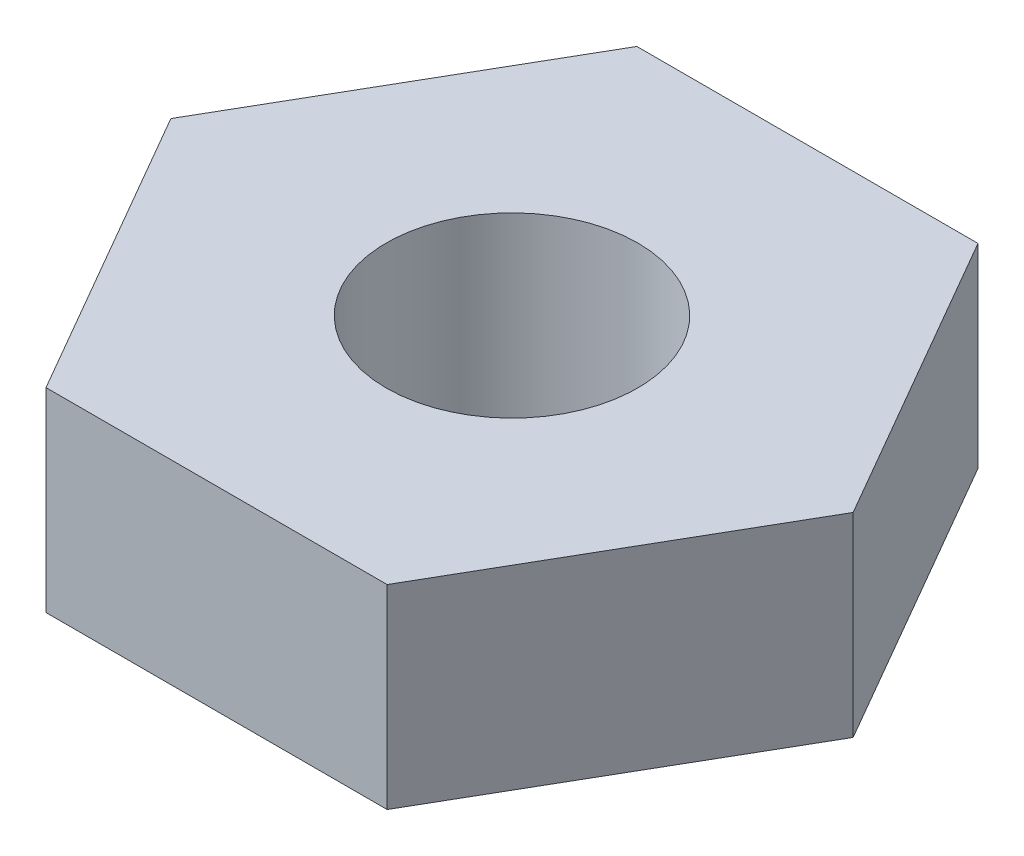
SolidWorks part; units mm, degrees
ref_plane "Front Plane" through (0, 0, 0) normal (0, 0, 1) x (1, 0, 0)
ref_plane "Top Plane" through (0, 0, 0) normal (0, 1, 0) x (1, 0, 0)
ref_plane "Right Plane" through (0, 0, 0) normal (1, 0, 0) x (0, 0, -1)
sketch "Sketch1" plane through (0, 0, 0) normal (0, 1, 0) x (1, 0, 0)
  line L1 (-2.7135, 4.7) -> (-5.4271, 0)
  line L2 (-5.4271, 0) -> (-2.7135, -4.7)
  line L3 (-2.7135, -4.7) -> (2.7135, -4.7)
  line L4 (2.7135, -4.7) -> (5.4271, 0)
  line L5 (5.4271, 0) -> (2.7135, 4.7)
  line L6 (2.7135, 4.7) -> (-2.7135, 4.7)
  circle A0 centre (0, 0) radius 2
  circle A1 centre (0, 0) radius 4.7 construction
  dimension "D2" = 4
  dimension "D1" = 9.4
extrude "Boss-Extrude1" add sketch "Sketch1" along normal blind 3.1
